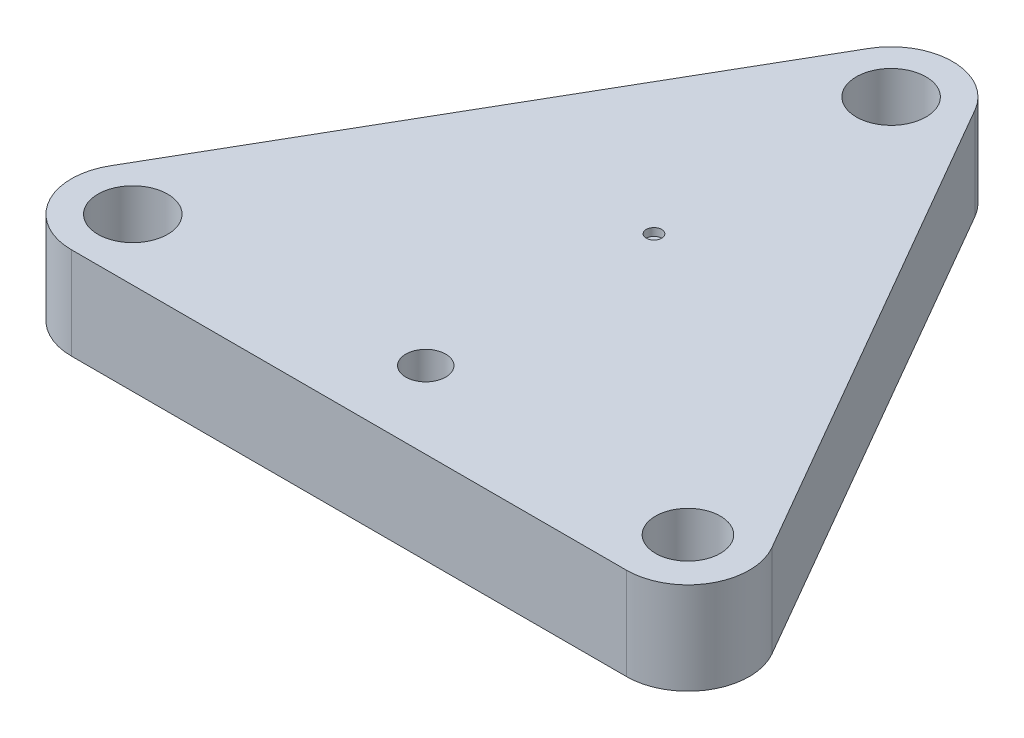
SolidWorks part; units mm, degrees
ref_plane "Front Plane" through (0, 0, 0) normal (0, 0, 1) x (1, 0, 0)
ref_plane "Top Plane" through (0, 0, 0) normal (0, 1, 0) x (1, 0, 0)
ref_plane "Right Plane" through (0, 0, 0) normal (1, 0, 0) x (0, 0, -1)
sketch "Sketch1" plane through (0, 0, 0) normal (0, 1, 0) x (1, 0, 0)
  line L0 (0, 0) -> (9.0359, 0)
  line L1 (10.7679, 3) -> (1.7321, 18.6506)
  line L2 (-1.7321, 18.6506) -> (-10.7679, 3)
  line L3 (-9.0359, 0) -> (0, 0)
  arc A0 (9.0359, 0) -> (10.7679, 3) centre (9.0359, 2) ccw
  arc A1 (-10.7679, 3) -> (-9.0359, 0) centre (-9.0359, 2) ccw
  arc A2 (1.7321, 18.6506) -> (-1.7321, 18.6506) centre (0, 17.6506) ccw
  circle A3 centre (0, 17.6506) radius 1.135
  circle A4 centre (-9.0359, 2) radius 1.135
  circle A5 centre (9.0359, 2) radius 1.054
  point P7 (12.5, 0)
  point P10 (-12.5, 0)
  point P13 (0, 21.6506)
  dimension "D5" = 2
  dimension "D1" = 60
  dimension "D2" = 60
  dimension "D3" = 25
  dimension "D4" = 12.5
extrude "Boss-Extrude1" add sketch "Sketch1" along normal blind 3
sketch "Sketch2" plane through (0, 3, 0) normal (0, 1, 0) x (1, 0, 0)
  line L0 (-9.0359, 0) -> (9.0359, 0) construction
  circle A1 centre (0, 2.5) radius 0.65
  point P7 (0, 0)
  dimension "D2" = 2.5
extrude "Cut-Extrude1" cut sketch "Sketch2" against normal through all
sketch "Sketch4" plane through (0, 3, 0) normal (0, 1, 0) x (1, 0, 0)
  circle A0 centre (0, 9.9304) radius 0.25
extrude "Cut-Extrude3" cut sketch "Sketch4" against normal blind 0.25
